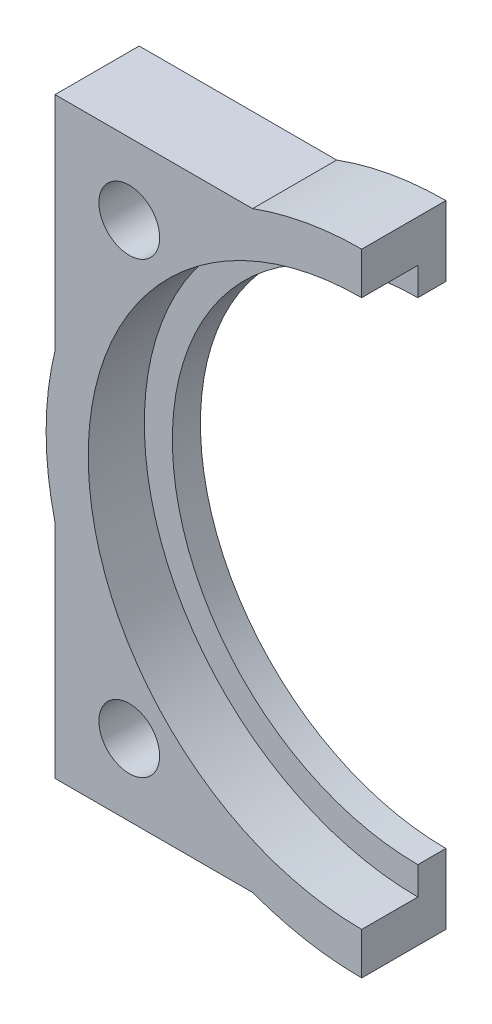
SolidWorks part; units mm, degrees
ref_plane "Front Plane" through (0, 0, 0) normal (0, 0, 1) x (1, 0, 0)
ref_plane "Top Plane" through (0, 0, 0) normal (0, 1, 0) x (1, 0, 0)
ref_plane "Right Plane" through (0, 0, 0) normal (1, 0, 0) x (0, 0, -1)
sketch "Sketch1" plane through (0, 0, 0) normal (0, 0, 1) x (1, 0, 0)
  circle A0 centre (0, 0) radius 17.4995
  circle A1 centre (0, 0) radius 22.4995
  dimension "D1" = 34.9991
  dimension "D2" = 5
extrude "Boss-Extrude1" add sketch "Sketch1" along normal blind 6
sketch "Sketch2" plane through (0, 0, 6) normal (0, 0, 1) x (1, 0, 0)
  circle A0 centre (0, 0) radius 19.4995
  circle A1 centre (0, 0) radius 17.4995
  dimension "D1" = 2
extrude "Cut-Extrude1" cut sketch "Sketch2" against normal blind 4
sketch "Sketch3" plane through (0, 0, 0) normal (0, 0, -1) x (-1, 0, 0)
  line L0 (-7.7836, 21.1103) -> (-21.8646, 21.1103)
  line L1 (21.8646, -21.1103) -> (7.7836, -21.1103)
  line L2 (21.8646, -21.1103) -> (21.8646, -5.3073)
  line L3 (21.8646, 21.1103) -> (7.7836, 21.1103)
  line L4 (-21.8646, -21.1103) -> (-21.8646, -5.3073)
  line L5 (21.8646, -21.1103) -> (-21.8646, 21.1103) construction
  line L6 (21.8646, 21.1103) -> (-21.8646, -21.1103) construction
  line L7 (16.5717, -16) -> (15.8186, -16) construction
  line L8 (16.5717, -16) -> (16.5717, 16) construction
  line L9 (16.5717, 16) -> (-16.5717, 16) construction
  line L10 (-16.5717, -16) -> (-16.5717, -15.2187) construction
  line L11 (16.5717, -16) -> (-16.5717, 16) construction
  line L12 (16.5717, 16) -> (-16.5717, -16) construction
  line L13 (21.8646, 5.3073) -> (21.8646, 21.1103)
  line L14 (-21.8646, 5.3073) -> (-21.8646, 21.1103)
  line L15 (-16.5717, 15.2187) -> (-16.5717, 16) construction
  line L16 (-15.8186, -16) -> (-16.5717, -16) construction
  line L17 (-7.7836, -21.1103) -> (-21.8646, -21.1103)
  arc A4 (-7.7836, 21.1103) -> (-21.8646, 5.3073) centre (0, 0) ccw
  arc A5 (21.8646, 5.3073) -> (7.7836, 21.1103) centre (0, 0) ccw
  arc A6 (-21.8646, -5.3073) -> (-7.7836, -21.1103) centre (0, 0) ccw
  arc A7 (7.7836, -21.1103) -> (21.8646, -5.3073) centre (0, 0) ccw
  circle A8 centre (0, 0) radius 22.4995 construction
  point P0 (0, 0)
  point P6 (0, 0)
  dimension "D1" = 42.2206
  dimension "D2" = 32
extrude "Boss-Extrude2" add sketch "Sketch3" against normal through all
sketch "Sketch5" plane through (0, 0, 0) normal (0, 0, -1) x (-1, 0, 0)
  line L0 (-14.4415, 9.8831) -> (-18.5678, 12.707)
  line L2 (-14.4415, -9.8831) -> (-18.5678, -12.707)
  line L4 (22.4995, 0) -> (0, 0) construction
  line L5 (-17.4995, 0) -> (-49.8767, 0) construction
  arc A0 (-18.5678, 12.707) -> (-18.5678, -12.707) centre (0, 0) ccw
  arc A1 (-14.4415, 9.8831) -> (-14.4415, -9.8831) centre (0, 0) ccw
extrude "Boss-Extrude3" add sketch "Sketch5" along normal blind 24
sketch "Sketch6" plane through (0, 0, -24) normal (0, 0, -1) x (-1, 0, 0)
  circle A0 centre (0, 0) radius 22.4995
  circle A1 centre (0, 0) radius 8.7945
  dimension "D1" = 17.5891
extrude "Boss-Extrude4" add sketch "Sketch6" along normal blind 5
sketch "Sketch7" plane through (0, 0, 0) normal (0, 0, -1) x (-1, 0, 0)
  line L0 (0, 20.425) -> (0, -31.8135)
  line L1 (0, -31.8135) -> (-34.413, -24.9639)
  line L2 (-34.413, -24.9639) -> (-30.3693, 32.3086)
  line L3 (-30.3693, 32.3086) -> (-0.6602, 29.5853)
  line L4 (0, 20.425) -> (0, 25.7891)
  line L5 (0, 25.7891) -> (-0.6602, 29.5853)
extrude "Cut-Extrude2" cut sketch "Sketch7" against normal mid plane 100
sketch "Sketch8" plane through (0, 0, 0) normal (1, 0, 0) x (0, 0, -1)
  line L1 (10.3116, 30.4518) -> (36.6537, 30.4518)
  line L2 (10.3116, 30.4518) -> (10.3116, -32.3334)
  line L3 (10.3116, -32.3334) -> (36.6537, -32.3334)
  line L4 (36.6537, 30.4518) -> (36.6537, -32.3334)
extrude "Cut-Extrude3" cut sketch "Sketch8" against normal through all
sketch "Sketch9" plane through (0, 0, 0) normal (0, 0, -1) x (-1, 0, 0)
  circle A0 centre (16.5717, 16) radius 2.165
  circle A1 centre (16.5717, -16) radius 2.165
  circle A2 centre (-16.5717, -16) radius 2.165
  circle A3 centre (-16.5717, 16) radius 2.165
  dimension "D1" = 4.33
extrude "Cut-Extrude4" cut sketch "Sketch9" against normal through all
